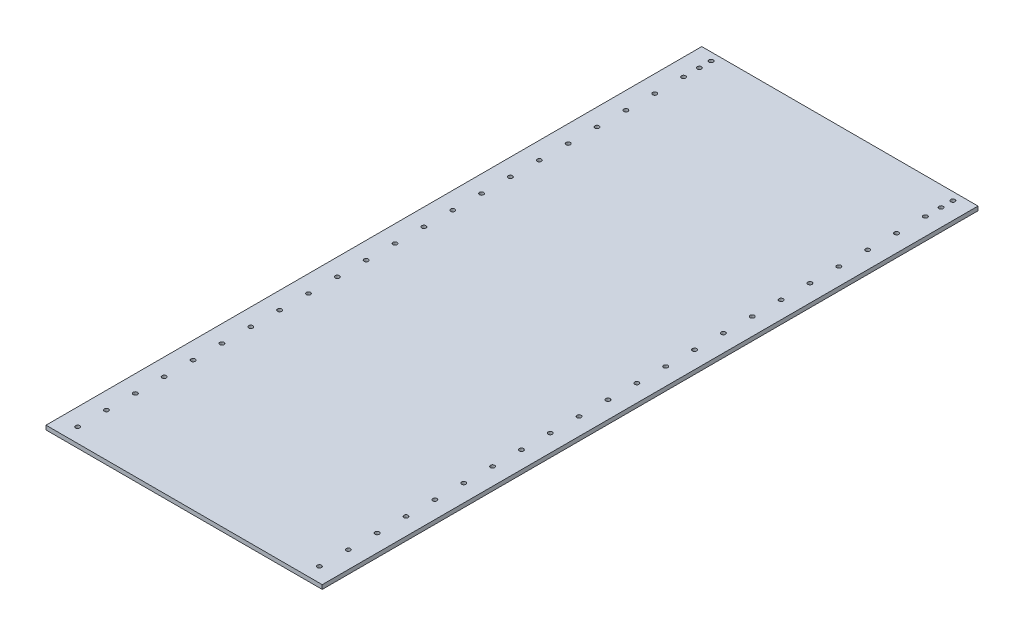
SolidWorks part; units mm, degrees
ref_plane "Front Plane" through (0, 0, 0) normal (0, 0, 1) x (1, 0, 0)
ref_plane "Top Plane" through (0, 0, 0) normal (0, 1, 0) x (1, 0, 0)
ref_plane "Right Plane" through (0, 0, 0) normal (1, 0, 0) x (0, 0, -1)
sketch "Sketch1" plane through (0, 0, 0) normal (0, 1, 0) x (1, 0, 0)
  line L0 (0, 250) -> (0, -250) construction
  line L1 (-105.305, -250) -> (105.305, -250)
  line L2 (-105.305, -250) -> (-105.305, 250)
  line L3 (-105.305, 250) -> (105.305, 250)
  line L4 (105.305, -250) -> (105.305, 250)
  line L5 (-105.305, -250) -> (105.305, 250) construction
  line L6 (-105.305, 250) -> (105.305, -250) construction
  circle A0 centre (92.18, 244) radius 1.6
  circle A1 centre (92.18, 235) radius 1.6
  circle A2 centre (92.18, 223) radius 1.6
  circle A3 centre (92.18, 201) radius 1.6
  circle A4 centre (92.18, 179) radius 1.6
  circle A5 centre (92.18, 157) radius 1.6
  circle A6 centre (92.18, 135) radius 1.6
  circle A7 centre (92.18, 113) radius 1.6
  circle A8 centre (92.18, 91) radius 1.6
  circle A9 centre (92.18, 69) radius 1.6
  circle A10 centre (92.18, 47) radius 1.6
  circle A11 centre (92.18, 25) radius 1.6
  circle A12 centre (92.18, 3) radius 1.6
  circle A13 centre (92.18, -19) radius 1.6
  circle A14 centre (92.18, -41) radius 1.6
  circle A15 centre (92.18, -63) radius 1.6
  circle A16 centre (92.18, -85) radius 1.6
  circle A17 centre (92.18, -107) radius 1.6
  circle A18 centre (92.18, -129) radius 1.6
  circle A19 centre (92.18, -151) radius 1.6
  circle A20 centre (92.18, -173) radius 1.6
  circle A21 centre (92.18, -195) radius 1.6
  circle A22 centre (92.18, -217) radius 1.6
  circle A23 centre (92.18, -239) radius 1.6
  circle A24 centre (-92.18, 69) radius 1.6
  circle A25 centre (-92.18, 91) radius 1.6
  circle A26 centre (-92.18, 113) radius 1.6
  circle A27 centre (-92.18, 135) radius 1.6
  circle A28 centre (-92.18, 157) radius 1.6
  circle A29 centre (-92.18, 179) radius 1.6
  circle A30 centre (-92.18, 201) radius 1.6
  circle A31 centre (-92.18, 223) radius 1.6
  circle A32 centre (-92.18, 235) radius 1.6
  circle A33 centre (-92.18, -239) radius 1.6
  circle A34 centre (-92.18, -217) radius 1.6
  circle A35 centre (-92.18, -195) radius 1.6
  circle A36 centre (-92.18, -173) radius 1.6
  circle A37 centre (-92.18, -151) radius 1.6
  circle A38 centre (-92.18, -129) radius 1.6
  circle A39 centre (-92.18, -107) radius 1.6
  circle A40 centre (-92.18, -85) radius 1.6
  circle A41 centre (-92.18, -63) radius 1.6
  circle A42 centre (-92.18, -41) radius 1.6
  circle A43 centre (-92.18, -19) radius 1.6
  circle A44 centre (-92.18, 3) radius 1.6
  circle A45 centre (-92.18, 25) radius 1.6
  circle A46 centre (-92.18, 47) radius 1.6
  circle A47 centre (-92.18, 244) radius 1.6
  point P0 (0, 0)
  dimension "D3" = 3.2
  dimension "D8" = 3.2
  dimension "D9" = 3.2
  dimension "D1" = 210.61
  dimension "D2" = 500
  dimension "D4" = 13.125
  dimension "D5" = 6
  dimension "D6" = 9
  dimension "D7" = 12
  dimension "D10" = 22
extrude "Boss-Extrude1" add sketch "Sketch1" along normal blind 3.175
equation "\"m3\"=3.2"
equation "\"D3@Sketch1\"=\"m3\""
equation "\"D8@Sketch1\"=\"m3\""
equation "\"D9@Sketch1\"=\"m3\""
